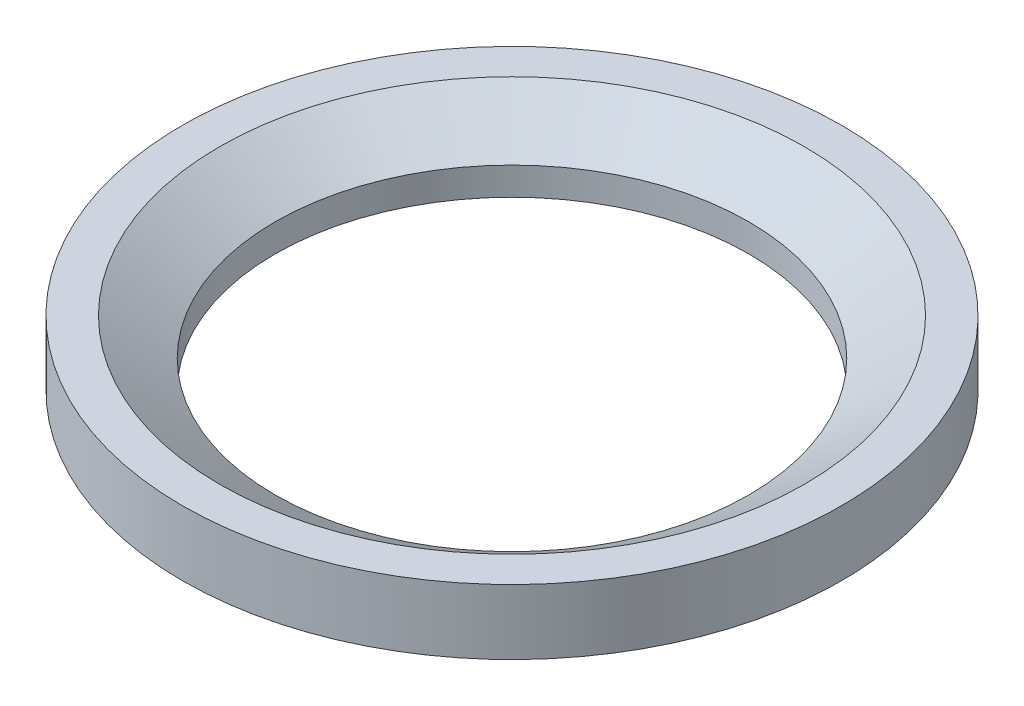
SolidWorks part; units mm, degrees
ref_plane "Front Plane" through (0, 0, 0) normal (0, 0, 1) x (1, 0, 0)
ref_plane "Top Plane" through (0, 0, 0) normal (0, 1, 0) x (1, 0, 0)
ref_plane "Right Plane" through (0, 0, 0) normal (1, 0, 0) x (0, 0, -1)
sketch "Sketch1" plane through (0, 0, 0) normal (0, 1, 0) x (1, 0, 0)
  circle A0 centre (0, 0) radius 25.5
  circle A1 centre (0, 0) radius 35.5
  dimension "D1" = 10
  dimension "51" = 51
extrude "Boss-Extrude1" add sketch "Sketch1" along normal blind 7
chamfer "Chamfer1" distance 6 distance2 4 1 edges at (0, 7, 25.5)
